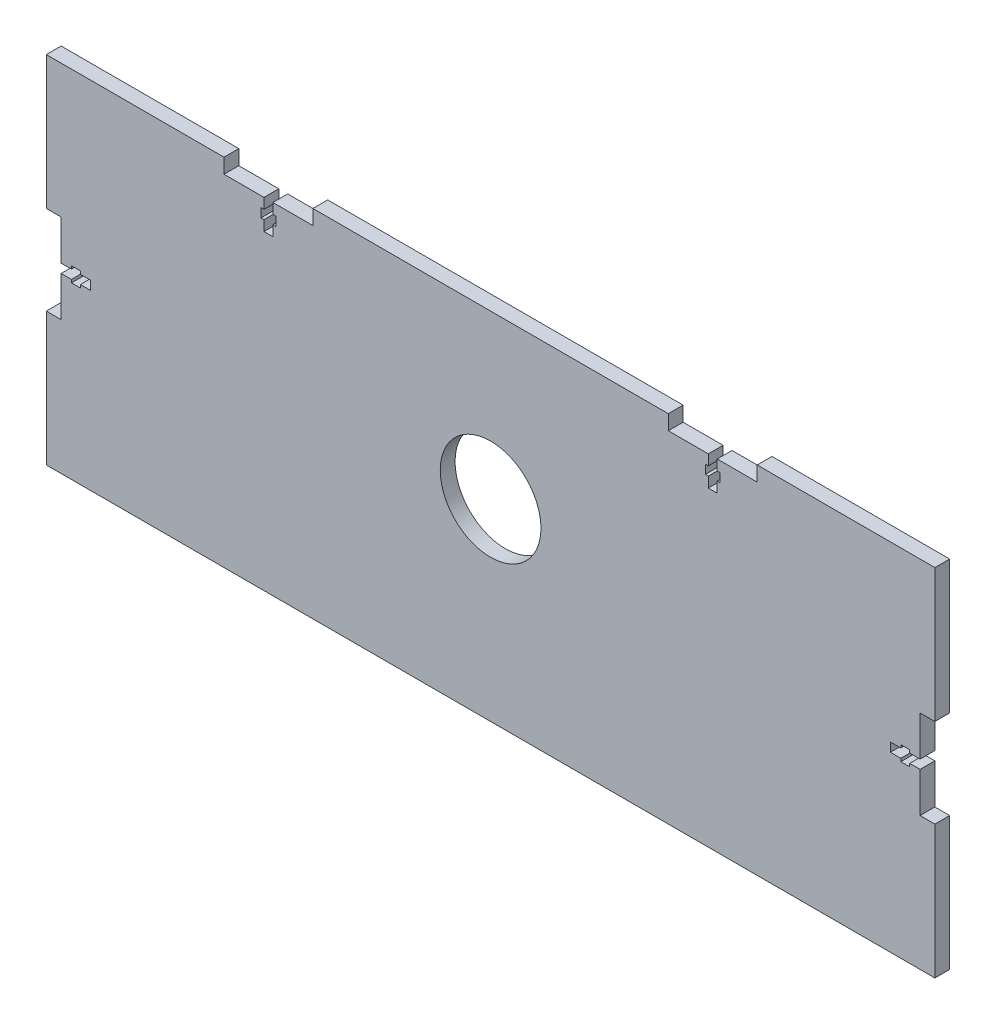
SolidWorks part; units mm, degrees
ref_plane "Plan de face" through (0, 0, 0) normal (0, 0, 1) x (1, 0, 0)
ref_plane "Plan de dessus" through (0, 0, 0) normal (0, 1, 0) x (1, 0, 0)
ref_plane "Plan de droite" through (0, 0, 0) normal (1, 0, 0) x (0, 0, -1)
sketch "Esquisse1" plane through (0, 0, 0) normal (0, 0, 1) x (1, 0, 0)
  line L0 (0, 198.5019) -> (0, -180.2838) construction
  line L1 (-150, 60) -> (150, 60)
  line L2 (-150, 60) -> (-150, -60)
  line L3 (-150, -60) -> (150, -60)
  line L4 (150, 60) -> (150, -60)
  line L5 (-150, 60) -> (150, -60) construction
  line L6 (-150, -60) -> (150, 60) construction
  line L7 (-75, 42.6575) -> (-75, 60) construction
  line L8 (-90, 60) -> (-60, 60)
  line L9 (-90, 60) -> (-90, 55)
  line L10 (-90, 55) -> (-60, 55)
  line L11 (-60, 60) -> (-60, 55)
  line L12 (-192.6201, 0) -> (197.1741, 0) construction
  line L13 (-76.5, 45) -> (-73.5, 45)
  line L14 (-76.5, 45) -> (-76.5, 55)
  line L15 (-76.5, 55) -> (-73.5, 55)
  line L16 (-73.5, 45) -> (-73.5, 55)
  line L17 (-76.5, 45) -> (-73.5, 55) construction
  line L18 (-76.5, 55) -> (-73.5, 45) construction
  line L19 (-77.5, 51.5) -> (-72.5, 51.5)
  line L20 (-77.5, 51.5) -> (-77.5, 48.5)
  line L21 (-77.5, 48.5) -> (-72.5, 48.5)
  line L22 (-72.5, 51.5) -> (-72.5, 48.5)
  line L23 (-77.5, 51.5) -> (-72.5, 48.5) construction
  line L24 (-77.5, 48.5) -> (-72.5, 51.5) construction
  line L25 (77.5, 48.5) -> (72.5, 48.5)
  line L26 (72.5, 51.5) -> (72.5, 48.5)
  line L27 (77.5, 51.5) -> (72.5, 51.5)
  line L28 (77.5, 51.5) -> (77.5, 48.5)
  line L29 (76.5, 55) -> (73.5, 55)
  line L30 (73.5, 45) -> (73.5, 55)
  line L31 (76.5, 45) -> (73.5, 45)
  line L32 (76.5, 45) -> (76.5, 55)
  line L33 (90, 55) -> (60, 55)
  line L34 (60, 60) -> (60, 55)
  line L35 (90, 60) -> (60, 60)
  line L36 (90, 60) -> (90, 55)
  line L46 (90, -60) -> (60, -60)
  line L59 (-90, -60) -> (-60, -60)
  line L61 (141.5, -2.5) -> (138.5, -2.5)
  line L62 (-145, 15) -> (-150, 15)
  line L63 (-145, 15) -> (-145, -15)
  line L64 (-145, -15) -> (-150, -15)
  line L65 (-150, 15) -> (-150, -15)
  line L66 (-145, 15) -> (-150, -15) construction
  line L67 (-145, -15) -> (-150, 15) construction
  line L68 (-135, 1.5) -> (-145, 1.5)
  line L69 (-135, 1.5) -> (-135, -1.5)
  line L70 (-135, -1.5) -> (-145, -1.5)
  line L71 (-145, 1.5) -> (-145, -1.5)
  line L72 (-135, 1.5) -> (-145, -1.5) construction
  line L73 (-135, -1.5) -> (-145, 1.5) construction
  line L74 (-141.5, 2.5) -> (-138.5, 2.5)
  line L75 (-141.5, 2.5) -> (-141.5, -2.5)
  line L76 (-141.5, -2.5) -> (-138.5, -2.5)
  line L77 (-138.5, 2.5) -> (-138.5, -2.5)
  line L78 (-141.5, 2.5) -> (-138.5, -2.5) construction
  line L79 (-141.5, -2.5) -> (-138.5, 2.5) construction
  line L80 (138.5, 2.5) -> (138.5, -2.5)
  line L81 (141.5, 2.5) -> (138.5, 2.5)
  line L82 (141.5, 2.5) -> (141.5, -2.5)
  line L83 (135, -1.5) -> (145, -1.5)
  line L84 (145, 1.5) -> (145, -1.5)
  line L85 (135, 1.5) -> (145, 1.5)
  line L86 (135, 1.5) -> (135, -1.5)
  line L87 (145, -15) -> (150, -15)
  line L88 (150, 15) -> (150, -15)
  line L89 (145, 15) -> (150, 15)
  line L90 (145, 15) -> (145, -15)
  point P0 (0, 0)
  point P12 (-75, 55)
  point P15 (-75, 50)
  point P20 (-75, 50)
  point P63 (-147.5, 0)
  point P68 (-140, 0)
  point P73 (-140, 0)
  dimension "D1" = 300
  dimension "D2" = 120
  dimension "D3" = 5
  dimension "D4" = 30
  dimension "D5" = 75
  dimension "D6" = 10
  dimension "D7" = 3
  dimension "D8" = 10
  dimension "D9" = 5
  dimension "D10" = 30
  dimension "D11" = 10
  dimension "D12" = 3
  dimension "D13" = 3
  dimension "D14" = 5
  dimension "D15" = 3
  dimension "D16" = 5
extrude "Boss.-Extru.1" add sketch "Esquisse1" along normal blind 5 contours L90 L89 L4 L1 L36 L33 L32 L27 L28 L25 L31 L30 L26 L34 L11 L10 L16 L19 L22 L21 L13 L14 L20 L9 L2 L62 L63 L68 L75 L74 L77 L69 L70 L76
sketch "Esquisse2" plane through (0, 0, 0) normal (0, 0, -1) x (-1, 0, 0)
  circle A0 centre (0, 5) radius 17
  dimension "D1" = 34
extrude "Enlèv. mat.-Extru.1" cut sketch "Esquisse2" against normal through all
